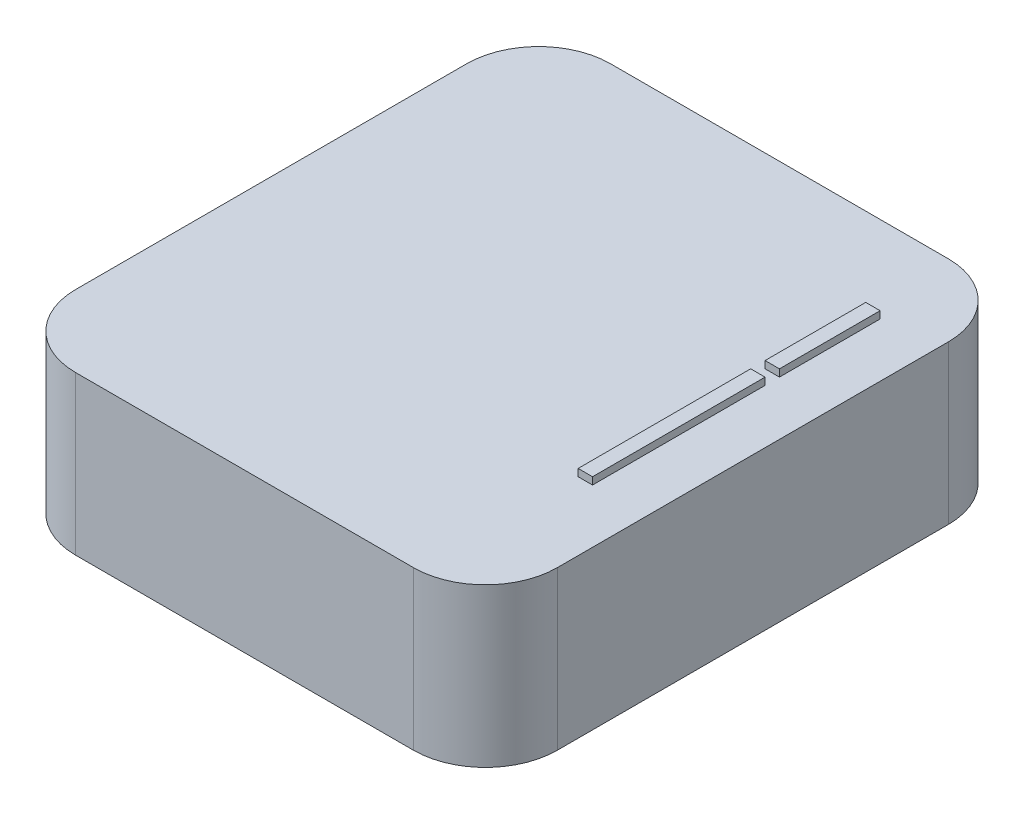
SolidWorks part; units mm, degrees
material "PE High Density"
ref_plane "Front Plane" through (0, 0, 0) normal (0, 0, 1) x (1, 0, 0)
ref_plane "Top Plane" through (0, 0, 0) normal (0, 1, 0) x (1, 0, 0)
ref_plane "Right Plane" through (0, 0, 0) normal (1, 0, 0) x (0, 0, -1)
sketch "Sketch1" plane through (0, 0, 0) normal (0, 1, 0) x (1, 0, 0)
  line L1 (-33.5, -37.2) -> (33.5, -37.2)
  line L2 (-33.5, -37.2) -> (-33.5, 37.2)
  line L3 (-33.5, 37.2) -> (33.5, 37.2)
  line L4 (33.5, -37.2) -> (33.5, 37.2)
  line L5 (-33.5, -37.2) -> (33.5, 37.2) construction
  line L6 (-33.5, 37.2) -> (33.5, -37.2) construction
  point P0 (0, 0)
  dimension "D1" = 74.4
  dimension "D2" = 67
extrude "Boss-Extrude1" add sketch "Sketch1" along normal blind 22
fillet "Fillet1" radius 10 4 edges at (-33.5, 11, -37.2) (33.5, 11, -37.2) (-33.5, 11, 37.2) (33.5, 11, 37.2)
sketch "Sketch2" plane through (0, 0, -37.2) normal (0, 0, -1) x (-1, 0, 0)
  line L0 (-33.5, 0) -> (-33.5, 22) construction
  line L1 (-12.5, 19) -> (2.5, 19)
  line L2 (-12.5, 19) -> (-12.5, 6)
  line L3 (-12.5, 6) -> (2.5, 6)
  line L4 (2.5, 19) -> (2.5, 6)
  line L5 (-12.5, 19) -> (2.5, 6) construction
  line L6 (-12.5, 6) -> (2.5, 19) construction
  line L7 (5.5, 10) -> (15.5, 10)
  line L8 (5.5, 10) -> (5.5, 5)
  line L9 (5.5, 5) -> (15.5, 5)
  line L10 (15.5, 10) -> (15.5, 5)
  line L11 (5.5, 10) -> (15.5, 5) construction
  line L12 (5.5, 5) -> (15.5, 10) construction
  line L13 (-23.5, 0) -> (23.5, 0) construction
  line L14 (-23.5, 22) -> (23.5, 22) construction
  point P0 (-5, 12.5)
  point P5 (10.5, 7.5)
  dimension "D1" = 13
  dimension "D2" = 15
  dimension "D3" = 10
  dimension "D4" = 5
  dimension "D5" = 3
  dimension "D6" = 5
  dimension "D7" = 3
  dimension "D8" = 21
extrude "Cut-Extrude1" cut sketch "Sketch2" against normal blind 10
sketch "Sketch3" plane through (0, 22, 0) normal (0, 1, 0) x (1, 0, 0)
  line L0 (33.5, -27.2) -> (33.5, 27.2) construction
  line L1 (24, 25.2) -> (26, 25.2)
  line L2 (24, 25.2) -> (24, 11.2)
  line L3 (24, 11.2) -> (26, 11.2)
  line L4 (26, 25.2) -> (26, 11.2)
  line L5 (24, 9.2) -> (26, 9.2)
  line L6 (24, 9.2) -> (24, -14.8)
  line L7 (24, -14.8) -> (26, -14.8)
  line L8 (26, 9.2) -> (26, -14.8)
  line L9 (26, 11.2) -> (26, 9.2) construction
  line L10 (23.5, 37.2) -> (-23.5, 37.2) construction
  dimension "D1" = 24
  dimension "D2" = 14
  dimension "D3" = 2
  dimension "D4" = 2
  dimension "D5" = 7.5
  dimension "D6" = 2
  dimension "D7" = 12
extrude "Boss-Extrude2" add sketch "Sketch3" along normal blind 1
